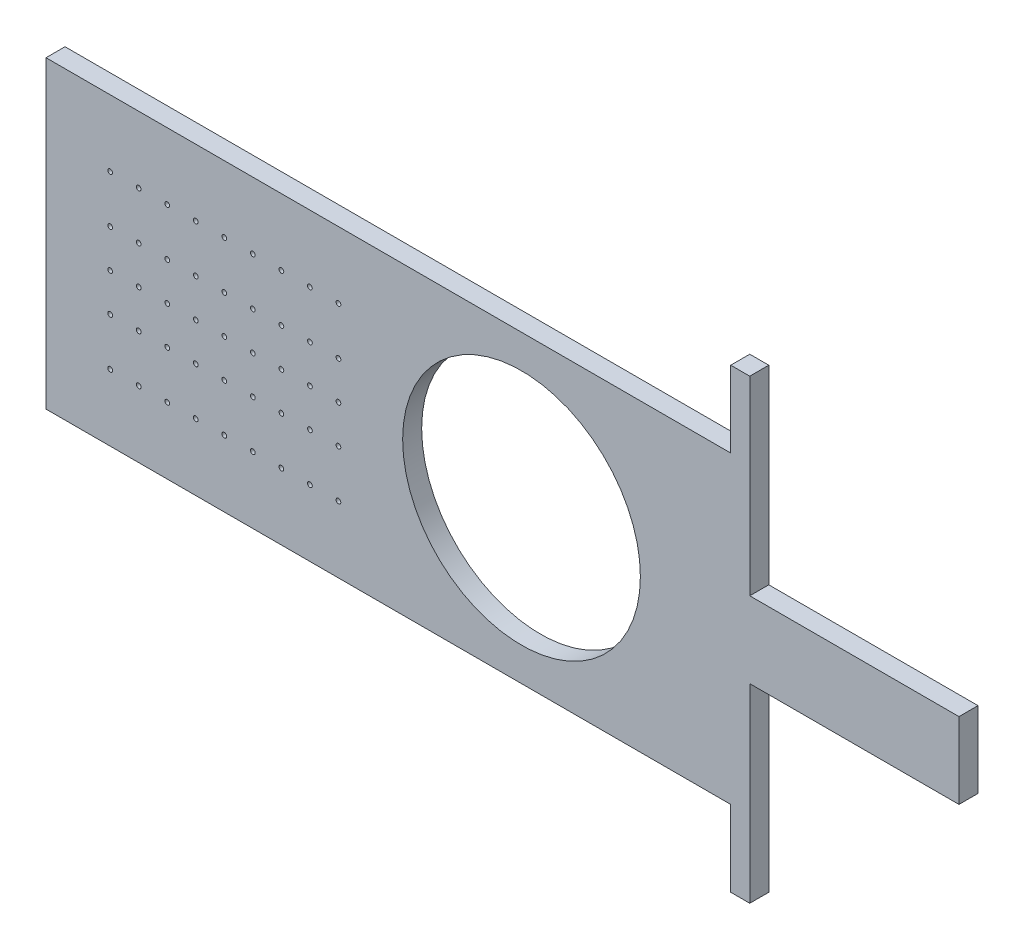
SolidWorks part; units mm, degrees
ref_plane "Front Plane" through (0, 0, 0) normal (0, 0, 1) x (1, 0, 0)
ref_plane "Top Plane" through (0, 0, 0) normal (0, 1, 0) x (1, 0, 0)
ref_plane "Right Plane" through (0, 0, 0) normal (1, 0, 0) x (0, 0, -1)
sketch "Sketch1" plane through (0, 0, 0) normal (0, 0, 1) x (1, 0, 0)
  line L1 (0, 0) -> (228.6, 0)
  line L2 (0, 0) -> (0, 101.6)
  line L3 (0, 101.6) -> (228.6, 101.6)
  line L4 (228.6, 0) -> (228.6, 101.6)
  dimension "D1" = 228.6
  dimension "D2" = 101.6
extrude "Boss-Extrude1" add sketch "Sketch1" along normal blind 6.35
sketch "Sketch2" plane through (0, 0, 6.35) normal (0, 0, 1) x (1, 0, 0)
  line L0 (228.6, 50.8) -> (88.9, 50.8)
  line L1 (228.6, 0) -> (228.6, 101.6) construction
  line L3 (228.6, 0) -> (228.6, 101.6) construction
  circle A0 centre (158.75, 50.8) radius 39.6875
  dimension "D1" = 69.85
  dimension "D2" = 79.375
extrude "Cut-Extrude1" cut sketch "Sketch2" against normal blind 76.2 contours L0 A0 | L0 A0
sketch "Sketch3" plane through (228.6, 0, 0) normal (1, 0, 0) x (0, 0, -1)
  line L0 (-6.35, 101.6) -> (-6.35, 63.5)
  line L1 (-6.35, 0) -> (-6.35, 101.6) construction
  line L2 (-6.35, 0) -> (-6.35, 38.1)
  line L3 (0, 0) -> (0, 101.6) construction
  line L4 (-6.35, 63.5) -> (0, 63.5)
  line L5 (-6.35, 63.5) -> (-6.35, 38.1)
  line L6 (-6.35, 38.1) -> (0, 38.1)
  line L7 (0, 63.5) -> (0, 38.1)
  line L8 (-6.35, 63.5) -> (0, 63.5)
  line L9 (0, 63.5) -> (0, 38.1)
  line L10 (0, 38.1) -> (-6.35, 38.1)
  line L11 (-6.35, 38.1) -> (-6.35, 63.5)
  line M1 (0, 0) -> (0, 101.6)
  line M3 (-6.35, 101.6) -> (-6.35, 0)
extrude "Boss-Extrude2" add sketch "Sketch3" along normal blind 76.2 contours L6 L4 M3 M1
sketch "Sketch5" plane through (0, 63.5, 0) normal (0, 1, 0) x (1, 0, 0)
  line L0 (228.6, -6.35) -> (234.95, -6.35)
  line L1 (304.8, -6.35) -> (228.6, -6.35) construction
  line L2 (234.95, -6.35) -> (234.95, 0)
  line L3 (304.8, 0) -> (228.6, 0) construction
  line L4 (234.95, 0) -> (228.6, 0)
  line L5 (228.6, 0) -> (228.6, -6.35)
  dimension "D1" = 6.35
extrude "Boss-Extrude3" add sketch "Sketch5" along normal blind 63.5
sketch "Sketch6" plane through (0, 38.1, 0) normal (0, -1, 0) x (1, 0, 0)
  line L0 (228.6, 6.35) -> (234.95, 6.35)
  line L1 (304.8, 6.35) -> (228.6, 6.35) construction
  line L2 (234.95, 6.35) -> (234.95, 0)
  line L3 (304.8, 0) -> (228.6, 0) construction
  line L4 (234.95, 0) -> (228.6, 0)
  line L5 (228.6, 0) -> (234.95, 0)
  dimension "D1" = 6.35
extrude "Boss-Extrude4" add sketch "Sketch6" along normal blind 63.5
sketch "Sketch7" plane through (0, 0, 6.35) normal (0, 0, 1) x (1, 0, 0)
  circle A0 centre (59.5312, 50.8) radius 0.7937
  circle A1 centre (59.5312, 79.375) radius 0.7937
  circle A2 centre (88.1063, 50.8) radius 0.7937
  circle A3 centre (59.5312, 38.1) radius 0.7937
  circle A4 centre (30.9563, 50.8) radius 0.7937
  circle A5 centre (50.0063, 50.8) radius 0.7937
  circle A6 centre (59.5312, 63.5) radius 0.7937
  circle A7 centre (78.5812, 50.8) radius 0.7938
  circle A8 centre (59.5312, 22.225) radius 0.7937
  circle A9 centre (97.6313, 50.8) radius 0.7937
  circle A10 centre (21.4313, 50.8) radius 0.7937
  circle A11 centre (69.0562, 79.375) radius 0.7937
  circle A12 centre (40.4813, 50.8) radius 0.7938
  circle A13 centre (69.0562, 63.5) radius 0.7937
  circle A14 centre (69.0563, 50.8) radius 0.7937
  circle A16 centre (69.0562, 38.1) radius 0.7937
  circle A18 centre (69.0562, 22.225) radius 0.7937
  circle A21 centre (78.5812, 79.375) radius 0.7937
  circle A23 centre (78.5812, 63.5) radius 0.7938
  circle A26 centre (78.5812, 38.1) radius 0.7938
  circle A28 centre (78.5812, 22.225) radius 0.7937
  circle A31 centre (88.1062, 79.375) radius 0.7937
  circle A33 centre (88.1062, 63.5) radius 0.7937
  circle A36 centre (88.1062, 38.1) radius 0.7937
  circle A38 centre (88.1062, 22.225) radius 0.7937
  circle A41 centre (97.6312, 79.375) radius 0.7937
  circle A43 centre (97.6312, 63.5) radius 0.7937
  circle A46 centre (97.6312, 38.1) radius 0.7937
  circle A48 centre (97.6312, 22.225) radius 0.7937
  circle A51 centre (21.4313, 22.225) radius 0.7937
  circle A53 centre (21.4313, 38.1) radius 0.7937
  circle A56 centre (21.4313, 63.5) radius 0.7937
  circle A58 centre (21.4313, 79.375) radius 0.7937
  circle A61 centre (30.9563, 22.225) radius 0.7937
  circle A63 centre (30.9563, 38.1) radius 0.7937
  circle A66 centre (30.9563, 63.5) radius 0.7937
  circle A68 centre (30.9563, 79.375) radius 0.7937
  circle A71 centre (40.4813, 22.225) radius 0.7937
  circle A73 centre (40.4813, 38.1) radius 0.7938
  circle A76 centre (40.4813, 63.5) radius 0.7938
  circle A78 centre (40.4813, 79.375) radius 0.7937
  circle A81 centre (50.0063, 22.225) radius 0.7937
  circle A83 centre (50.0063, 38.1) radius 0.7937
  circle A86 centre (50.0063, 63.5) radius 0.7937
  circle A88 centre (50.0063, 79.375) radius 0.7937
  dimension "D1" = 5
extrude "Cut-Extrude3" cut sketch "Sketch7" against normal blind 50.8
